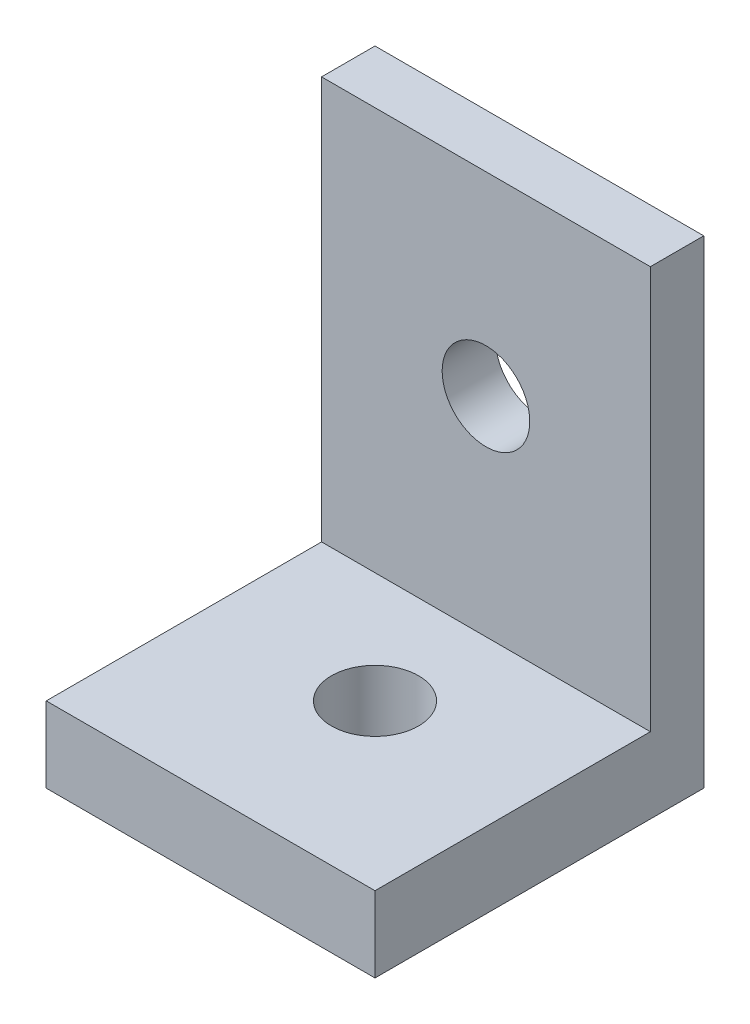
SolidWorks part; units mm, degrees
ref_plane "Front Plane" through (0, 0, 0) normal (0, 0, 1) x (1, 0, 0)
ref_plane "Top Plane" through (0, 0, 0) normal (0, 1, 0) x (1, 0, 0)
ref_plane "Right Plane" through (0, 0, 0) normal (1, 0, 0) x (0, 0, -1)
sketch "Sketch1" plane through (0, 0, 0) normal (0, 1, 0) x (1, 0, 0)
  line L1 (-10, -10) -> (10, -10)
  line L2 (-10, -10) -> (-10, 10)
  line L3 (-10, 10) -> (10, 10)
  line L4 (10, -10) -> (10, 10)
  line L5 (-10, -10) -> (10, 10) construction
  line L6 (-10, 10) -> (10, -10) construction
  circle A0 centre (0, 0) radius 2.65
  point P0 (0, 0)
  dimension "D3" = 5.3
  dimension "D1" = 20
  dimension "D2" = 20
extrude "Boss-Extrude1" add sketch "Sketch1" along normal blind 4.6
sketch "Sketch2" plane through (0, 4.6, 0) normal (0, 1, 0) x (1, 0, 0)
  line L0 (10, -10) -> (10, 10) construction
  line L1 (-10, 10) -> (10, 10)
  line L2 (-10, 10) -> (-10, 6.75)
  line L3 (-10, 6.75) -> (10, 6.75)
  line L4 (10, 10) -> (10, 6.75)
  dimension "D1" = 3.25
extrude "Boss-Extrude2" add sketch "Sketch2" along normal blind 24.5
sketch "Sketch3" plane through (0, 0, -10) normal (0, 0, -1) x (-1, 0, 0)
  line L3 (-10, 29.1) -> (10, 29.1) construction
  circle A0 centre (0, 17.275) radius 2.665
  dimension "D1" = 5.33
  dimension "D2" = 9.16
extrude "Cut-Extrude1" cut sketch "Sketch3" against normal through all
